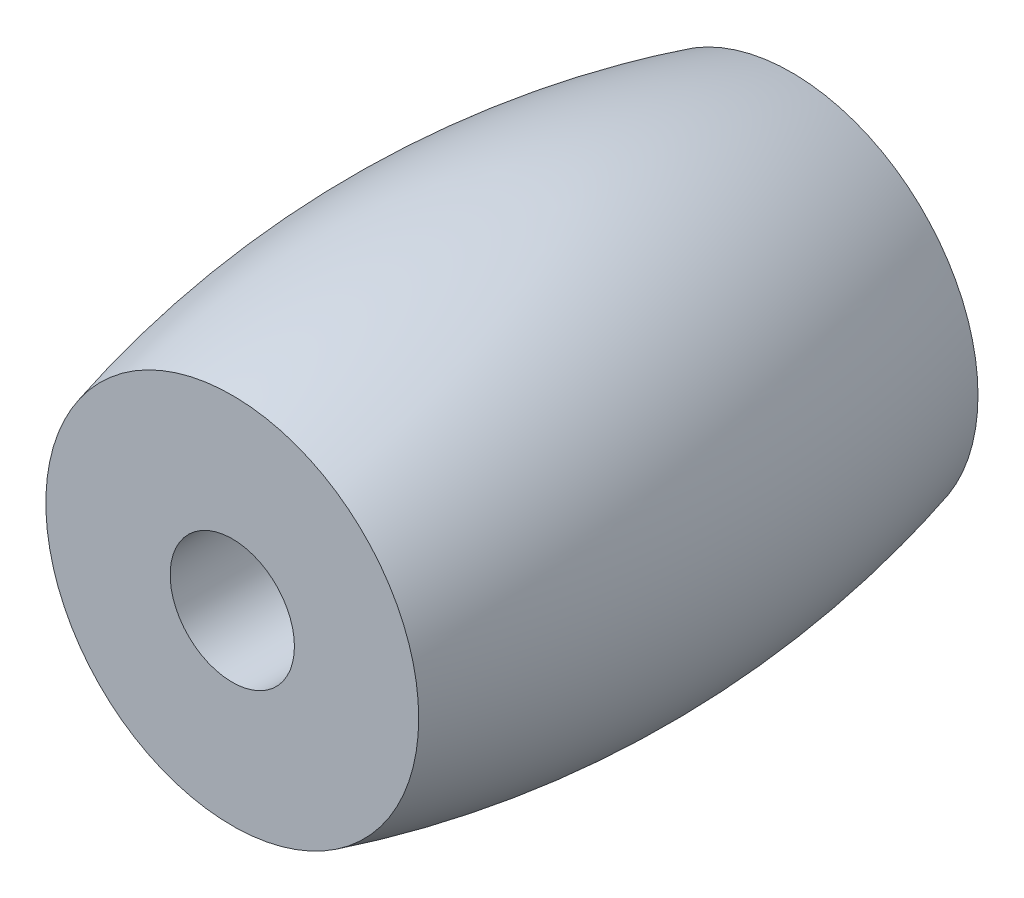
SolidWorks part; units mm, degrees
material "EPDM 60 硬度计"
ref_plane "前视基准面" through (0, 0, 0) normal (0, 0, 1) x (1, 0, 0)
ref_plane "上视基准面" through (0, 0, 0) normal (0, 1, 0) x (1, 0, 0)
ref_plane "右视基准面" through (0, 0, 0) normal (1, 0, 0) x (0, 0, -1)
sketch "草图1" plane through (0, 0, 0) normal (0, 1, 0) x (1, 0, 0)
  line L0 (4.5, 6.75) -> (1.5, 6.75)
  line L1 (1.5, 6.75) -> (1.5, -6.75)
  line L2 (1.5, -6.75) -> (4.5, -6.75)
  line L3 (0, 6.75) -> (0, -6.75) construction
  arc A0 (4.5, -6.75) -> (4.5, 6.75) centre (-20.3625, 0) ccw
revolve "旋转1" add sketch "草图1" angle 360 about L3
